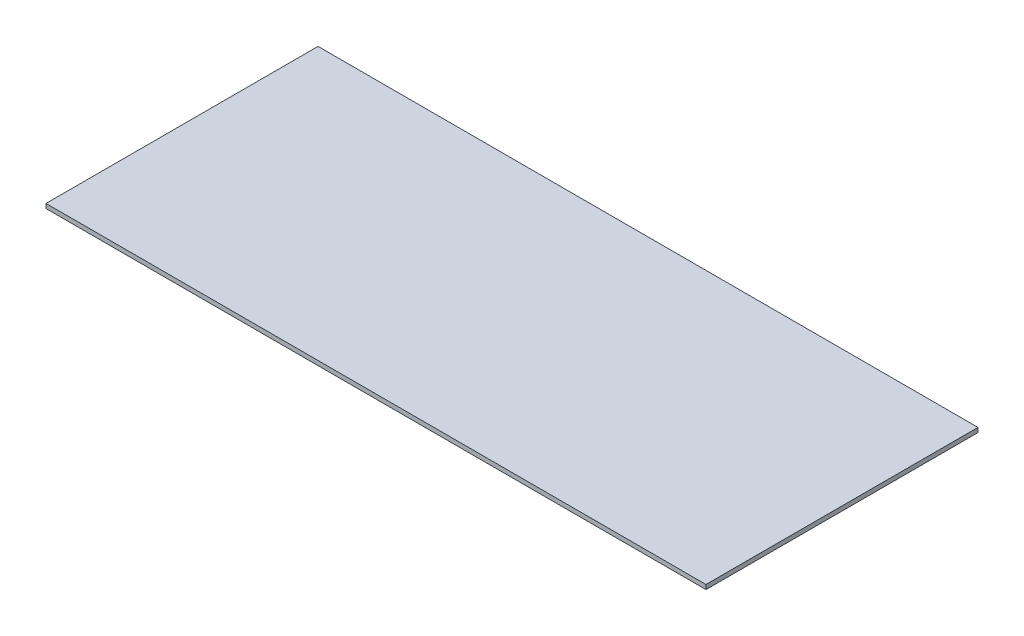
SolidWorks part; units mm, degrees
material "Бальса"
ref_plane "Спереди" through (0, 0, 0) normal (0, 0, 1) x (1, 0, 0)
ref_plane "Сверху" through (0, 0, 0) normal (0, 1, 0) x (1, 0, 0)
ref_plane "Справа" through (0, 0, 0) normal (1, 0, 0) x (0, 0, -1)
sketch "Эскиз1" plane through (0, 0, 0) normal (0, 1, 0) x (1, 0, 0)
  line L1 (0, 0) -> (1480, 0)
  line L2 (0, 0) -> (0, 610)
  line L3 (0, 610) -> (1480, 610)
  line L4 (1480, 0) -> (1480, 610)
  dimension "D1" = 610
  dimension "D2" = 1480
extrude "Бобышка-Вытянуть1" add sketch "Эскиз1" along normal blind 10
